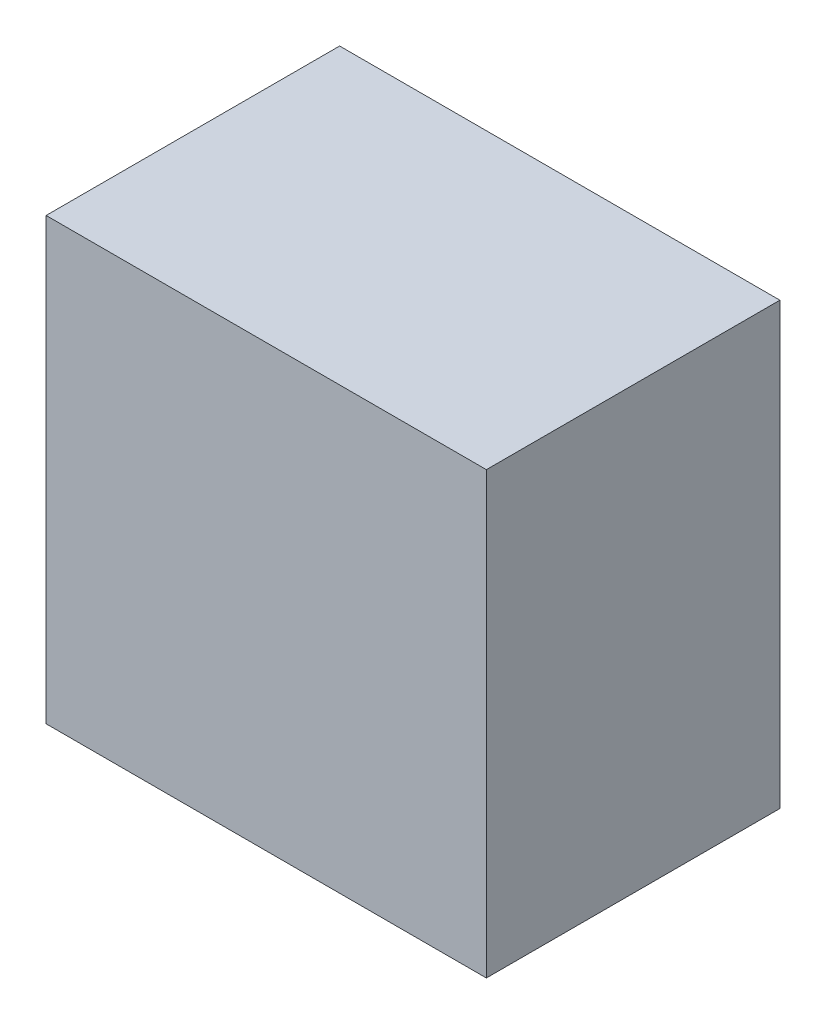
SolidWorks part; units mm, degrees
ref_plane "Front Plane" through (0, 0, 0) normal (0, 0, 1) x (1, 0, 0)
ref_plane "Top Plane" through (0, 0, 0) normal (0, 1, 0) x (1, 0, 0)
ref_plane "Right Plane" through (0, 0, 0) normal (1, 0, 0) x (0, 0, -1)
sketch "Sketch1" plane through (0, 0, 0) normal (0, 0, 1) x (1, 0, 0)
  line L1 (0, 0) -> (38.1, 0)
  line L2 (0, 0) -> (0, -38.1)
  line L3 (0, -38.1) -> (38.1, -38.1)
  line L4 (38.1, 0) -> (38.1, -38.1)
  dimension "D1" = 38.1
  dimension "D2" = 38.1
extrude "Boss-Extrude1" add sketch "Sketch1" along normal blind 25.4
